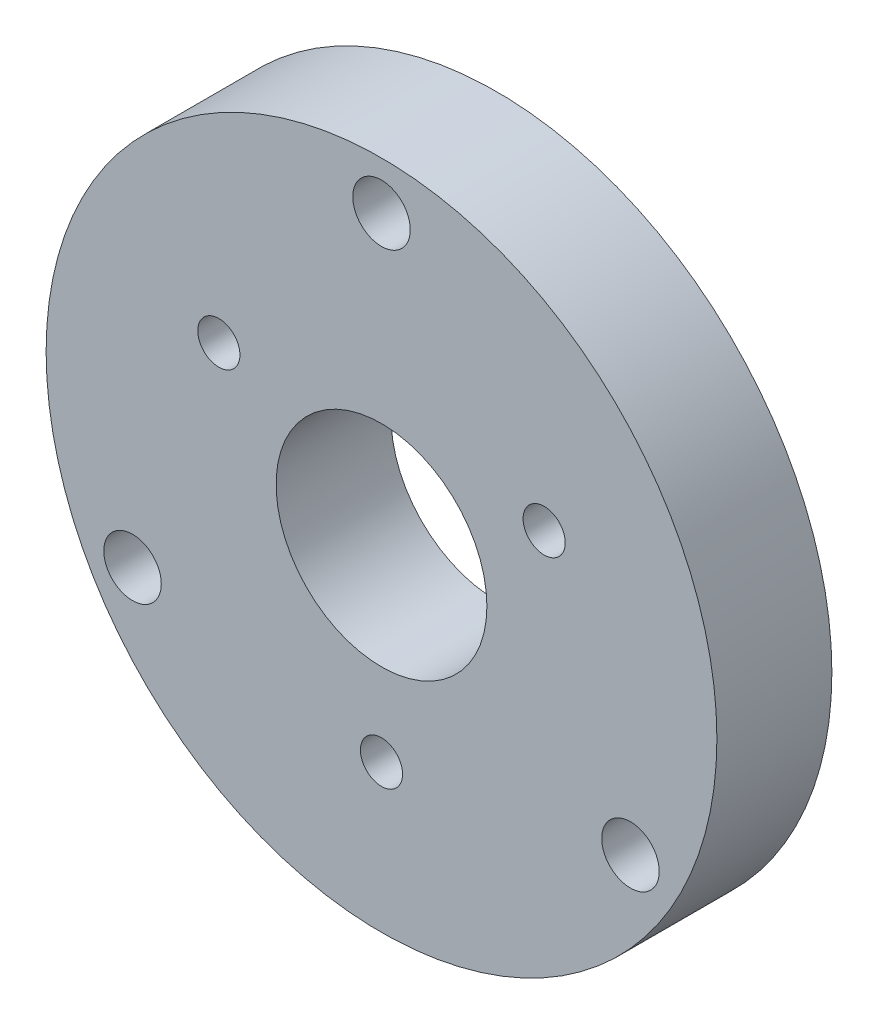
SolidWorks part; units mm, degrees
ref_plane "前视基准面" through (0, 0, 0) normal (0, 0, 1) x (1, 0, 0)
ref_plane "上视基准面" through (0, 0, 0) normal (0, 1, 0) x (1, 0, 0)
ref_plane "右视基准面" through (0, 0, 0) normal (1, 0, 0) x (0, 0, -1)
sketch "草图1" plane through (0, 0, 0) normal (0, 0, 1) x (1, 0, 0)
  circle A0 centre (0, 0) radius 17.5
  circle A1 centre (0, 0) radius 15 construction
  circle A2 centre (0, 15) radius 1.5
  circle A3 centre (12.9904, -7.5) radius 1.5
  circle A4 centre (-12.9904, -7.5) radius 1.5
  circle A5 centre (0, 0) radius 5.5
  point P12 (0, 0)
  dimension "D1" = 35
  dimension "D2" = 30
  dimension "D3" = 3
  dimension "D5" = 11
  dimension "D4" = 3
extrude "凸台-拉伸1" add sketch "草图1" along normal blind 6
sketch "草图2" plane through (0, 0, 0) normal (0, 0, 1) x (1, 0, 0)
  line L0 (0, 21.0688) -> (0, -21.9453) construction
  line L1 (0, 0) -> (-22.3304, 12.8925) construction
  circle A0 centre (0, 0) radius 9.8 construction
  circle A1 centre (-8.487, 4.9) radius 1.1
  circle A2 centre (8.487, 4.9) radius 1.1
  circle A3 centre (0, -9.8) radius 1.1
  point P15 (0, 0)
  dimension "D2" = 19.6
  dimension "D3" = 2.2
  dimension "D1" = 60
  dimension "D4" = 3
extrude "切除-拉伸1" cut sketch "草图2" along normal blind 19
